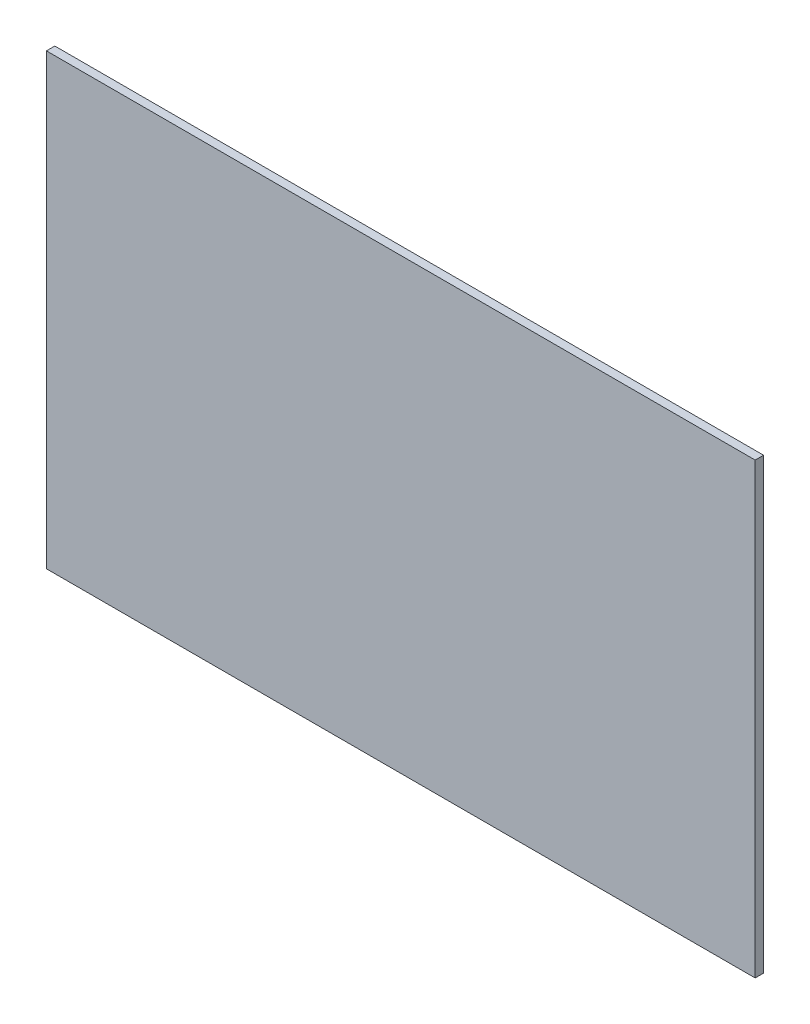
SolidWorks part; units mm, degrees
material "Pino"
ref_plane "Alzado" through (0, 0, 0) normal (0, 0, 1) x (1, 0, 0)
ref_plane "Planta" through (0, 0, 0) normal (0, 1, 0) x (1, 0, 0)
ref_plane "Vista lateral" through (0, 0, 0) normal (1, 0, 0) x (0, 0, -1)
sketch "Croquis1" plane through (0, 0, 0) normal (0, 0, 1) x (1, 0, 0)
  line L1 (-183.8771, -134.785) -> (69.3458, -134.785)
  line L2 (-183.8771, -134.785) -> (-183.8771, 25.4643)
  line L3 (-183.8771, 25.4643) -> (69.3458, 25.4643)
  line L4 (69.3458, -134.785) -> (69.3458, 25.4643)
  line L5 (-183.8771, -134.785) -> (69.3458, 25.4643) construction
  line L6 (-183.8771, 25.4643) -> (69.3458, -134.785) construction
  point P0 (-57.2656, -54.6604)
extrude "Saliente-Extruir1" add sketch "Croquis1" along normal blind 3
